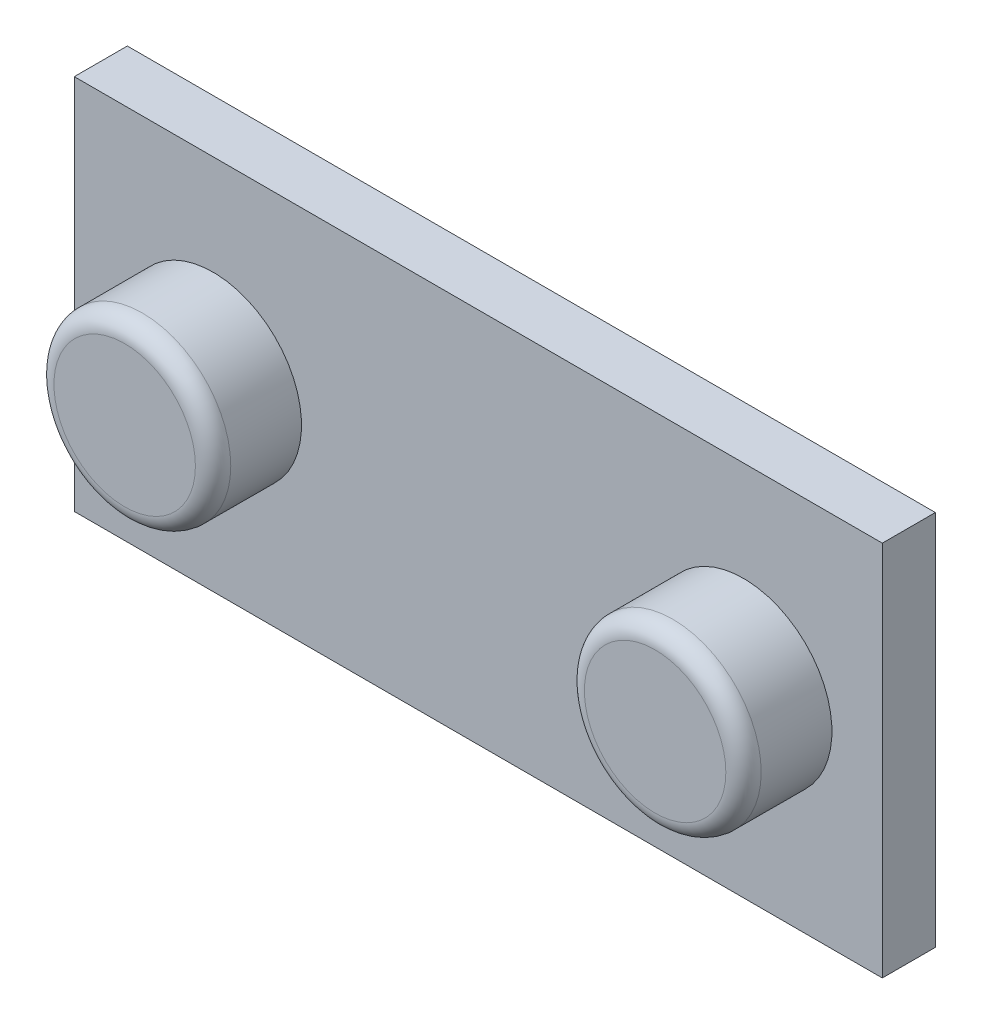
SolidWorks part; units mm, degrees
ref_plane "Front Plane" through (0, 0, 0) normal (0, 0, 1) x (1, 0, 0)
ref_plane "Top Plane" through (0, 0, 0) normal (0, 1, 0) x (1, 0, 0)
ref_plane "Right Plane" through (0, 0, 0) normal (1, 0, 0) x (0, 0, -1)
sketch "Sketch1" plane through (0, 0, 0) normal (0, 0, 1) x (1, 0, 0)
  line L1 (-22.85, -10.65) -> (22.85, -10.65)
  line L2 (-22.85, -10.65) -> (-22.85, 10.65)
  line L3 (-22.85, 10.65) -> (22.85, 10.65)
  line L4 (22.85, -10.65) -> (22.85, 10.65)
  line L5 (-22.85, -10.65) -> (22.85, 10.65) construction
  line L6 (-22.85, 10.65) -> (22.85, -10.65) construction
  point P0 (0, 0)
  dimension "D1" = 45.7
  dimension "D2" = 21.3
extrude "Boss-Extrude1" add sketch "Sketch1" along normal blind 3
sketch "Sketch2" plane through (0, 0, 3) normal (0, 0, 1) x (1, 0, 0)
  circle A0 centre (-15, 0) radius 5
  circle A1 centre (15, 0) radius 5
  dimension "D1" = 15
  dimension "D3" = 10
  dimension "D4" = 10
  dimension "D2" = 15
extrude "Boss-Extrude2" add sketch "Sketch2" along normal blind 5
fillet "Fillet1" radius 1 2 edges at (-10, 0, 8) (20, 0, 8)
